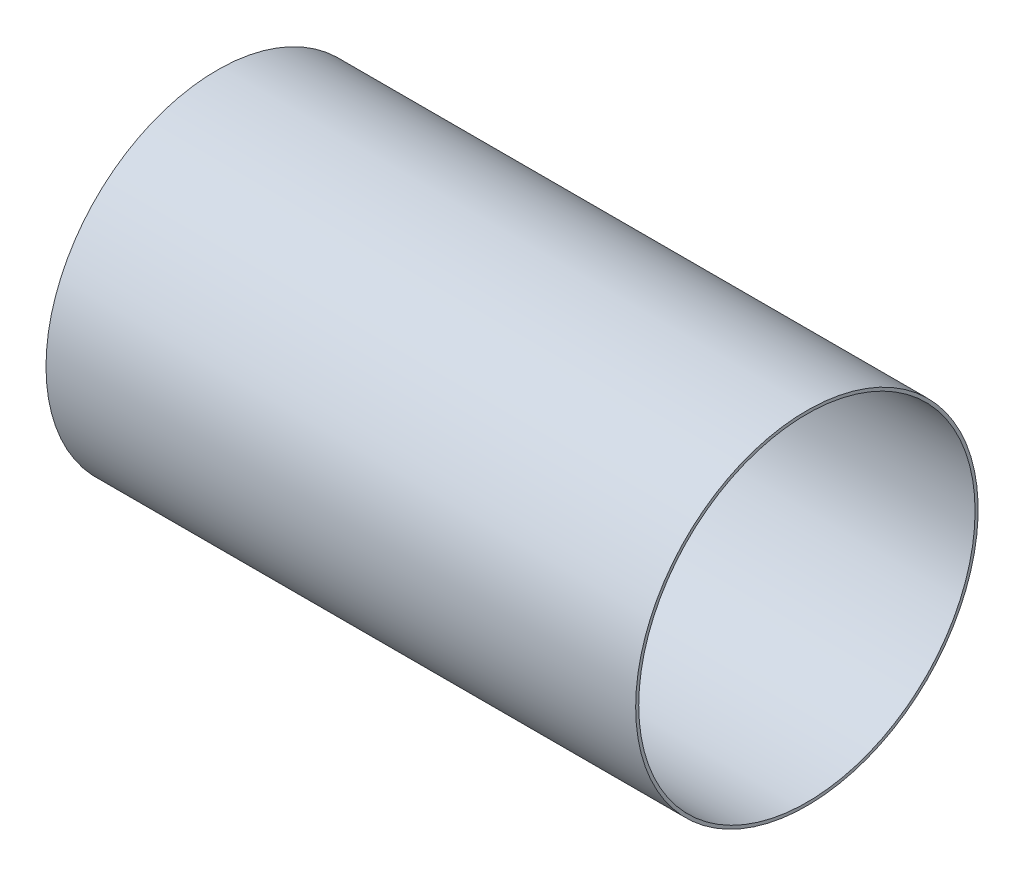
SolidWorks part; units mm, degrees
ref_plane "Front Plane" through (0, 0, 0) normal (1, 0, 0) x (0, 1, 0)
ref_plane "Top Plane" through (0, 0, 0) normal (0, 0, 1) x (0, 1, 0)
ref_plane "Right Plane" through (0, 0, 0) normal (0, 1, 0) x (-1, 0, 0)
sketch "Sketch1" plane through (0, 0, 0) normal (1, 0, 0) x (0, 1, 0)
  circle A0 centre (0, 0) radius 88.519
  circle A1 centre (0, 0) radius 86.9315
  dimension "D1" = 177.038
  dimension "D2" = 173.863
extrude "Boss-Extrude1" add sketch "Sketch1" along normal blind 304.8
